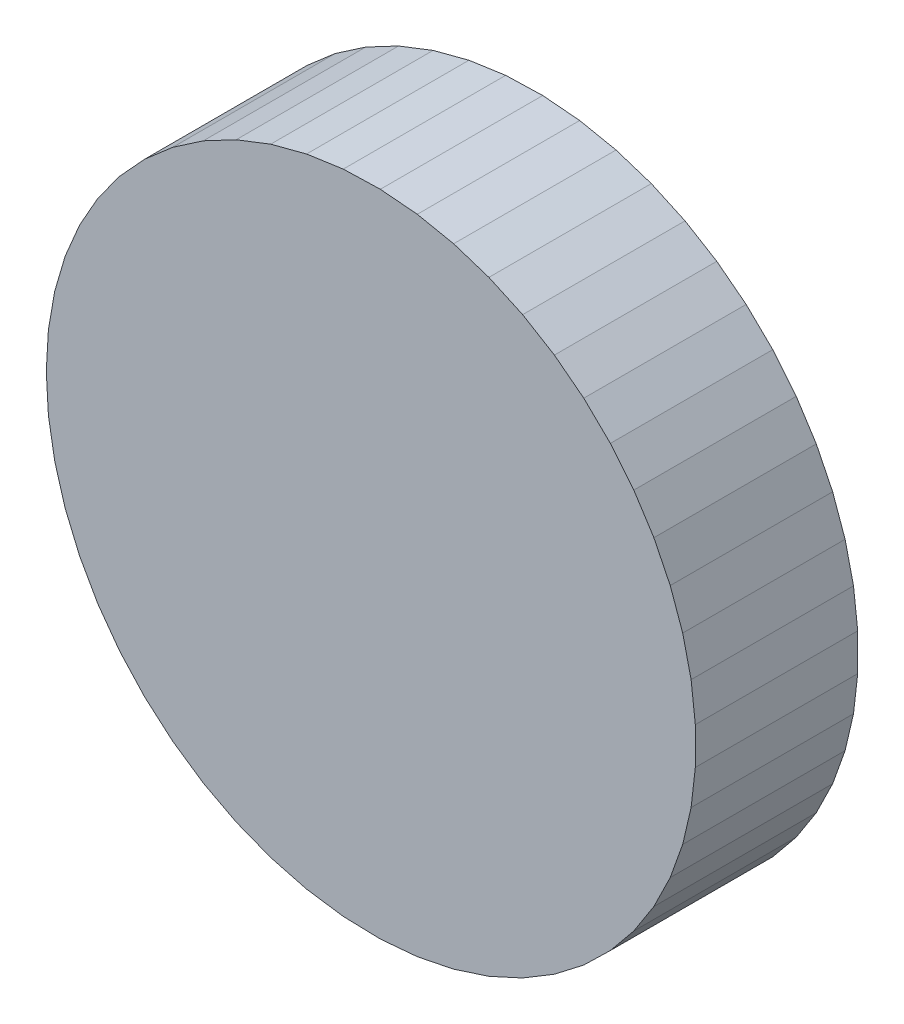
SolidWorks part; units mm, degrees
ref_plane "Front Plane" through (0, 0, 0) normal (0, 0, 1) x (1, 0, 0)
ref_plane "Top Plane" through (0, 0, 0) normal (0, 1, 0) x (1, 0, 0)
ref_plane "Right Plane" through (0, 0, 0) normal (1, 0, 0) x (0, 0, -1)
sketch "Biên dạng ngoài theo phôi gốc" plane through (0, 0, 0) normal (0, 0, 1) x (1, 0, 0)
  line L0 (-20, 0) -> (-19.8696, -2.2798)
  line L1 (-19.8696, -2.2798) -> (-19.4802, -4.5299)
  line L2 (-19.4802, -4.5299) -> (-18.8369, -6.721)
  line L3 (-18.8369, -6.721) -> (-17.948, -8.8244)
  line L4 (-17.948, -8.8244) -> (-16.8251, -10.8128)
  line L5 (-16.8251, -10.8128) -> (-15.4828, -12.6602)
  line L6 (-15.4828, -12.6602) -> (-13.9388, -14.3426)
  line L7 (-13.9388, -14.3426) -> (-12.213, -15.838)
  line L8 (-12.213, -15.838) -> (-10.3279, -17.127)
  line L9 (-10.3279, -17.127) -> (-8.3083, -18.1926)
  line L10 (-8.3083, -18.1926) -> (-6.1803, -19.0211)
  line L11 (-6.1803, -19.0211) -> (-3.9718, -19.6017)
  line L12 (-3.9718, -19.6017) -> (-1.7115, -19.9266)
  line L13 (-1.7115, -19.9266) -> (0.5711, -19.9918)
  line L14 (0.5711, -19.9918) -> (2.8463, -19.7964)
  line L15 (2.8463, -19.7964) -> (5.0844, -19.3429)
  line L16 (5.0844, -19.3429) -> (7.2562, -18.6373)
  line L17 (7.2562, -18.6373) -> (9.3333, -17.6887)
  line L18 (9.3333, -17.6887) -> (11.2889, -16.5094)
  line L19 (11.2889, -16.5094) -> (13.0972, -15.115)
  line L20 (13.0972, -15.115) -> (14.7348, -13.5235)
  line L21 (14.7348, -13.5235) -> (16.1803, -11.7557)
  line L22 (16.1803, -11.7557) -> (17.4149, -9.8347)
  line L23 (17.4149, -9.8347) -> (18.4225, -7.7854)
  line L24 (18.4225, -7.7854) -> (19.1899, -5.6347)
  line L25 (19.1899, -5.6347) -> (19.7071, -3.4104)
  line L26 (19.7071, -3.4104) -> (19.9674, -1.1418)
  line L27 (19.9674, -1.1418) -> (19.9674, 1.1418)
  line L28 (19.9674, 1.1418) -> (19.7071, 3.4104)
  line L29 (19.7071, 3.4104) -> (19.1899, 5.6347)
  line L30 (19.1899, 5.6347) -> (18.4225, 7.7854)
  line L31 (18.4225, 7.7854) -> (17.4149, 9.8347)
  line L32 (17.4149, 9.8347) -> (16.1803, 11.7557)
  line L33 (16.1803, 11.7557) -> (14.7348, 13.5235)
  line L34 (14.7348, 13.5235) -> (13.0972, 15.115)
  line L35 (13.0972, 15.115) -> (11.2889, 16.5094)
  line L36 (11.2889, 16.5094) -> (9.3333, 17.6887)
  line L37 (9.3333, 17.6887) -> (7.2562, 18.6373)
  line L38 (7.2562, 18.6373) -> (5.0844, 19.3429)
  line L39 (5.0844, 19.3429) -> (2.8463, 19.7964)
  line L40 (2.8463, 19.7964) -> (0.5711, 19.9918)
  line L41 (0.5711, 19.9918) -> (-1.7115, 19.9266)
  line L42 (-1.7115, 19.9266) -> (-3.9718, 19.6017)
  line L43 (-3.9718, 19.6017) -> (-6.1803, 19.0211)
  line L44 (-6.1803, 19.0211) -> (-8.3083, 18.1926)
  line L45 (-8.3083, 18.1926) -> (-10.3279, 17.127)
  line L46 (-10.3279, 17.127) -> (-12.213, 15.838)
  line L47 (-12.213, 15.838) -> (-13.9388, 14.3426)
  line L48 (-13.9388, 14.3426) -> (-15.4828, 12.6602)
  line L49 (-15.4828, 12.6602) -> (-16.8251, 10.8128)
  line L50 (-16.8251, 10.8128) -> (-17.948, 8.8244)
  line L51 (-17.948, 8.8244) -> (-18.8369, 6.721)
  line L52 (-18.8369, 6.721) -> (-19.4802, 4.5299)
  line L53 (-19.4802, 4.5299) -> (-19.8696, 2.2798)
  line L54 (-19.8696, 2.2798) -> (-20, 0)
extrude "Thân ngoài" add sketch "Biên dạng ngoài theo phôi gốc" along normal blind 10
sketch "Biên dạng trong cách thành ngoài 0,3 mm" plane through (0, 0, 0) normal (0, 0, 1) x (1, 0, 0)
  line L0 (-19.5711, -2.2456) -> (-19.1876, -4.4619)
  line L1 (-19.1876, -4.4619) -> (-18.5539, -6.62)
  line L2 (-18.5539, -6.62) -> (-17.6783, -8.6918)
  line L3 (-17.6783, -8.6918) -> (-16.5723, -10.6504)
  line L4 (-16.5723, -10.6504) -> (-15.2502, -12.47)
  line L5 (-15.2502, -12.47) -> (-13.7293, -14.1271)
  line L6 (-13.7293, -14.1271) -> (-12.0295, -15.6001)
  line L7 (-12.0295, -15.6001) -> (-10.1728, -16.8697)
  line L8 (-10.1728, -16.8697) -> (-8.1835, -17.9193)
  line L9 (-8.1835, -17.9193) -> (-6.0875, -18.7353)
  line L10 (-6.0875, -18.7353) -> (-3.9121, -19.3071)
  line L11 (-3.9121, -19.3071) -> (-1.6858, -19.6272)
  line L12 (-1.6858, -19.6272) -> (0.5625, -19.6915)
  line L13 (0.5625, -19.6915) -> (2.8035, -19.499)
  line L14 (2.8035, -19.499) -> (5.008, -19.0523)
  line L15 (5.008, -19.0523) -> (7.1471, -18.3573)
  line L16 (7.1471, -18.3573) -> (9.1931, -17.4229)
  line L17 (9.1931, -17.4229) -> (11.1193, -16.2614)
  line L18 (11.1193, -16.2614) -> (12.9004, -14.8879)
  line L19 (12.9004, -14.8879) -> (14.5134, -13.3203)
  line L20 (14.5134, -13.3203) -> (15.9372, -11.5791)
  line L21 (15.9372, -11.5791) -> (17.1533, -9.6869)
  line L22 (17.1533, -9.6869) -> (18.1457, -7.6684)
  line L23 (18.1457, -7.6684) -> (18.9015, -5.55)
  line L24 (18.9015, -5.55) -> (19.411, -3.3592)
  line L25 (19.411, -3.3592) -> (19.6674, -1.1246)
  line L26 (19.6674, -1.1246) -> (19.6674, 1.1246)
  line L27 (19.6674, 1.1246) -> (19.411, 3.3592)
  line L28 (19.411, 3.3592) -> (18.9015, 5.55)
  line L29 (18.9015, 5.55) -> (18.1457, 7.6684)
  line L30 (18.1457, 7.6684) -> (17.1533, 9.6869)
  line L31 (17.1533, 9.6869) -> (15.9372, 11.5791)
  line L32 (15.9372, 11.5791) -> (14.5134, 13.3203)
  line L33 (14.5134, 13.3203) -> (12.9004, 14.8879)
  line L34 (12.9004, 14.8879) -> (11.1193, 16.2614)
  line L35 (11.1193, 16.2614) -> (9.1931, 17.4229)
  line L36 (9.1931, 17.4229) -> (7.1471, 18.3573)
  line L37 (7.1471, 18.3573) -> (5.008, 19.0523)
  line L38 (5.008, 19.0523) -> (2.8035, 19.499)
  line L39 (2.8035, 19.499) -> (0.5625, 19.6915)
  line L40 (0.5625, 19.6915) -> (-1.6858, 19.6272)
  line L41 (-1.6858, 19.6272) -> (-3.9121, 19.3071)
  line L42 (-3.9121, 19.3071) -> (-6.0875, 18.7353)
  line L43 (-6.0875, 18.7353) -> (-8.1835, 17.9193)
  line L44 (-8.1835, 17.9193) -> (-10.1728, 16.8697)
  line L45 (-10.1728, 16.8697) -> (-12.0295, 15.6001)
  line L46 (-12.0295, 15.6001) -> (-13.7293, 14.1271)
  line L47 (-13.7293, 14.1271) -> (-15.2502, 12.47)
  line L48 (-15.2502, 12.47) -> (-16.5723, 10.6504)
  line L49 (-16.5723, 10.6504) -> (-17.6783, 8.6918)
  line L50 (-17.6783, 8.6918) -> (-18.5539, 6.62)
  line L51 (-18.5539, 6.62) -> (-19.1876, 4.4619)
  line L52 (-19.1876, 4.4619) -> (-19.5711, 2.2456)
  line L53 (-19.5711, 2.2456) -> (-19.6995, 0)
  line L54 (-19.6995, 0) -> (-19.5711, -2.2456)
extrude "Khoang rỗng kín" cut sketch "Biên dạng trong cách thành ngoài 0,3 mm" along normal blind 9 from offset 0.5
